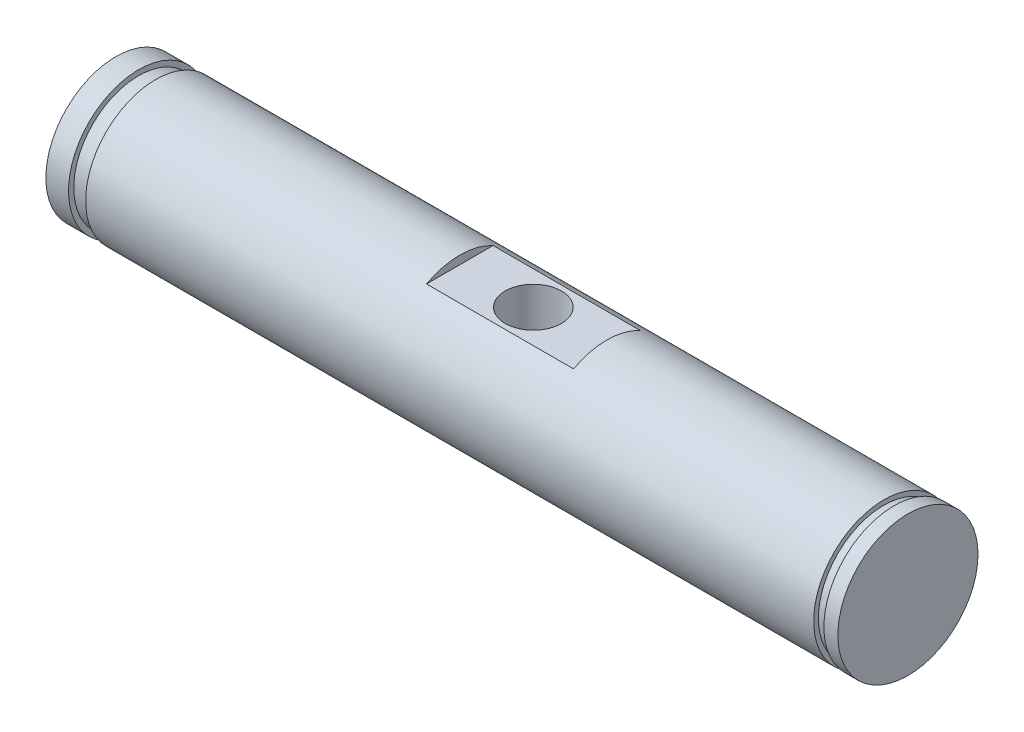
SolidWorks part; units mm, degrees
ref_plane "Front Plane" through (0, 0, 0) normal (0, 0, 1) x (1, 0, 0)
ref_plane "Top Plane" through (0, 0, 0) normal (0, 1, 0) x (1, 0, 0)
ref_plane "Right Plane" through (0, 0, 0) normal (1, 0, 0) x (0, 0, -1)
sketch "Sketch1" plane through (0, 0, 0) normal (1, 0, 0) x (0, 0, -1)
  circle A0 centre (0, 0) radius 6.35
  dimension "D1" = 12.7
extrude "Boss-Extrude1" add sketch "Sketch1" along normal blind 28.575
ref_axis "Axis1" through (28.575, 0, 0) along (-1, 0, 0)
sketch "Sketch2" plane through (0, 0, 0) normal (0, 0, 1) x (1, 0, 0)
  line L0 (26.3862, 6.35) -> (26.3862, 5.9246)
  line L1 (28.575, 6.35) -> (0, 6.35) construction
  line L2 (26.3862, 5.9246) -> (27.3109, 5.9246)
  line L3 (27.3109, 5.9246) -> (27.3109, 6.35)
  line L4 (27.3109, 6.35) -> (26.3862, 6.35)
revolve "Cut-Revolve1" cut sketch "Sketch2" angle 360 about axis through (28.575, 0, 0) along (-1, 0, 0)
sketch "Sketch7" plane through (0, 0, 0) normal (1, 0, 0) x (0, 0, -1)
  circle A0 centre (0, 0) radius 6.35
  dimension "D1" = 12.7
extrude "Boss-Extrude3" add sketch "Sketch7" against normal blind 43.18
sketch "Sketch8" plane through (0, 0, 0) normal (0, 0, 1) x (1, 0, 0)
  line L0 (-41.1267, 6.35) -> (-41.1267, 5.877)
  line L1 (26.3862, 6.35) -> (-43.18, 6.35) construction
  line L2 (-41.1267, 5.877) -> (-39.5777, 5.877)
  line L3 (-39.5777, 5.877) -> (-39.5777, 6.35)
  line L5 (-39.5777, 6.35) -> (-41.1267, 6.35)
  point P4 (-39.5777, 5.877)
revolve "Cut-Revolve2" cut sketch "Sketch8" angle 360 about axis through (28.575, 0, 0) along (-1, 0, 0)
ref_plane "Plane2" through (0, 6.35, 0) normal (0, 1, 0) x (1, 0, 0)
hole_wizard "1/4-20 Tapped Hole2" positions "Sketch15" profile "Sketch16" tap size "1/4-20" standard "ANSI Inch" end condition through all
sketch "Sketch15" plane through (0, 6.35, 0) normal (0, 1, 0) x (1, 0, 0)
  line L0 (28.575, 0) -> (-44.98, 0) construction
  line L1 (26.3862, -5.9246) -> (26.3862, 5.9246) construction
  point P0 (-5.3638, 0)
  dimension "D1" = 31.75
sketch "Sketch16" plane through (-5.3638, 6.35, 0) normal (1, 0, 0) x (0, 0, 1)
  line L0 (0, 0) -> (0, 12.7)
  line L1 (0, 12.7) -> (2.5527, 12.7)
  line L2 (2.5527, 12.7) -> (2.5527, 0)
  line L5 (2.5527, 0) -> (0, 0)
  line L11 (0, -6.35) -> (0, 107.95) construction
  dimension "Thru Tap Drill Dia." = 5.1054
  dimension "Thru Tap Drill Depth" = 12.7
cosmetic thread "Hole Thread3" parameters "D2"=6.35
sketch "Sketch17" plane through (0, 6.35, 0) normal (0, 1, 0) x (1, 0, 0)
  line L1 (1.2985, 4.495) -> (-12.0261, 4.495)
  line L2 (1.2985, 4.495) -> (1.2985, -4.495)
  line L3 (1.2985, -4.495) -> (-12.0261, -4.495)
  line L4 (-12.0261, 4.495) -> (-12.0261, -4.495)
  line L5 (1.2985, 4.495) -> (-12.0261, -4.495) construction
  line L6 (1.2985, -4.495) -> (-12.0261, 4.495) construction
  point P0 (-5.3638, 0)
extrude "Cut-Extrude3" cut sketch "Sketch17" against normal blind 0.762
